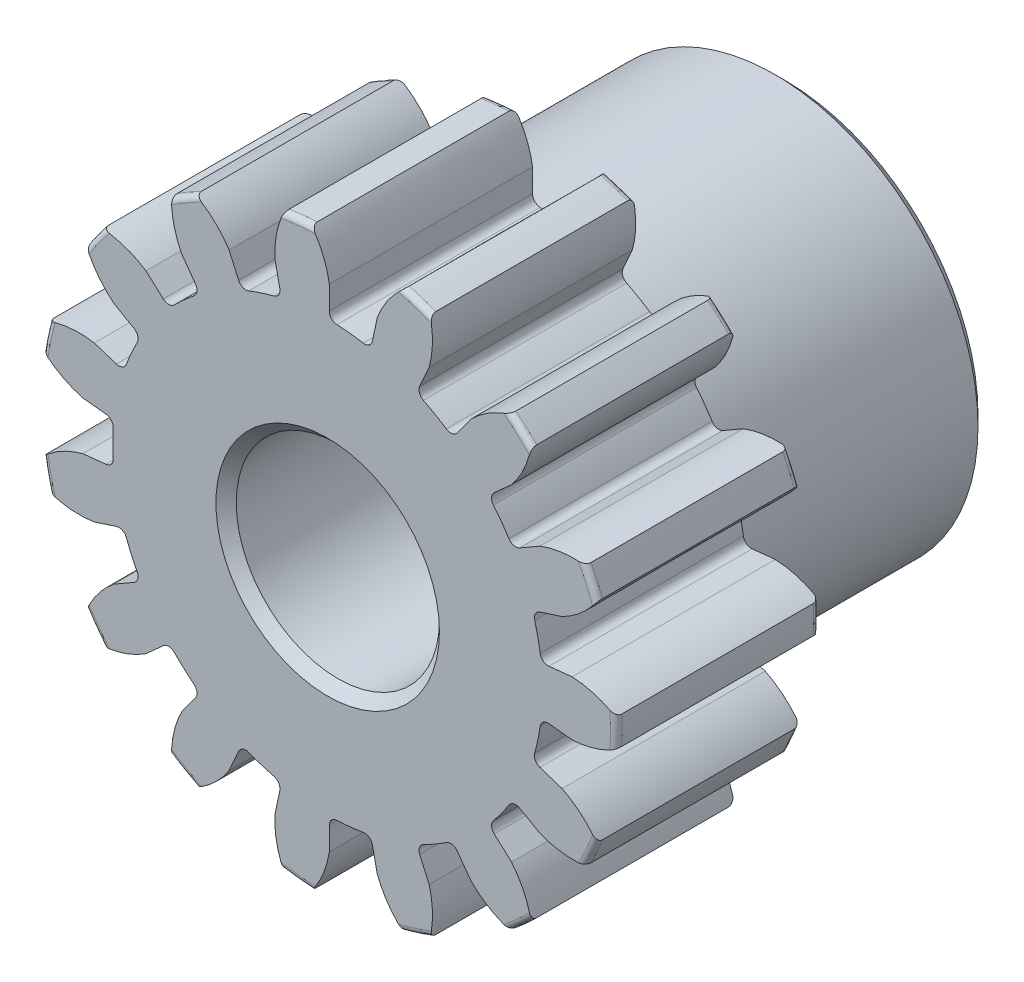
SolidWorks part; units mm, degrees
ref_plane "Front" through (0, 0, 0) normal (0, 0, 1) x (1, 0, 0)
ref_plane "Top" through (0, 0, 0) normal (0, 1, 0) x (1, 0, 0)
ref_plane "Right" through (0, 0, 0) normal (1, 0, 0) x (0, 0, -1)
sketch "Sketch1" plane through (0, 0, 0) normal (0, 0, 1) x (1, 0, 0)
  line L0 (-190.5, 0) -> (190.5, 0) construction
  circle A0 centre (0, 0) radius 9.017
  circle A1 centre (0, 0) radius 7.9375 construction
  circle A3 centre (0, 0) radius 6.713 construction
  dimension "D1" = 1.2245
  dimension "D2" = 2.304
  dimension "D3" = 1.0795
extrude "Boss-Extrude1" add sketch "Sketch1" against normal blind 6.35
sketch "Sketch2" plane through (0, 0, 0) normal (1, 0, 0) x (0, 0, -1)
  line L0 (6.35, 0) -> (14.2875, 0)
  line L1 (6.35, 0) -> (6.35, 6.35)
  line L2 (6.35, 6.35) -> (14.2875, 6.35)
  line L3 (14.2875, 6.35) -> (14.2875, 0)
  point P5 (14.2875, -6.35)
revolve "Revolve1" add sketch "Sketch2" angle 360 mid plane about L0
fillet "Fillet2" radius 0.1803 3 edges at (9.017, 0, -6.35) (9.017, 0, 0) (6.35, 0, -6.35)
sketch "Sketch3" plane through (0, 0, 0) normal (0, 0, 1) x (1, 0, 0)
  line L0 (0, 0) -> (0, 9.017) construction
  line L1 (-1.9241, 7.4399) -> (0, 7.9375)
  line L2 (-9.5921, 7.9375) -> (9.5921, 7.9375) construction
  line L3 (-9.2865, 5.5358) -> (9.2865, 10.3392) construction
  line L4 (-1.9241, 7.4399) -> (0, 0) construction
  line L5 (-4.7531, 6.0384) -> (0, 0) construction
  line L6 (-4.7531, 6.0384) -> (-0.6929, 9.2344) construction
  line L7 (-1.3417, 7.5666) -> (0, 0) construction
  line L8 (-1.3417, 7.5666) -> (0.0282, 7.8095) construction
  arc A0 (-1.9241, 7.4399) -> (-4.7531, 6.0384) centre (0, 0) ccw
  circle A1 centre (0, 0) radius 7.9375 construction
  circle A2 centre (0, 0) radius 7.6847 construction
  arc A3 (-1.9241, 7.4399) -> (-1.3417, 7.5666) centre (0, 0) cw
  circle A4 centre (0, 0) radius 9.017 construction
  point P6 (0, 7.9375)
  dimension "D1" = 1.9874
  dimension "D3" = 5.1672
  dimension "D5" = 1.3912
  dimension "D2" = 3.1798
  dimension "D4" = 0.5962
sketch "Sketch4" plane through (0, 0, 0) normal (0, 0, 1) x (1, 0, 0)
  line L0 (0, 0) -> (0.8252, 7.8508) construction
  line L1 (0.0499, 7.6845) -> (0.0499, 6.7128)
  line L2 (0, 7.9375) -> (1.6503, 7.764) construction
  line L3 (1.5489, 7.527) -> (1.3468, 6.5765)
  line L4 (0.0499, 6.7128) -> (0, 0) construction
  line L5 (0, 0) -> (0, 9.017) construction
  arc A0 (1.3468, 6.5765) -> (0.0499, 6.7128) centre (0, 0) ccw
  arc A1 (0, 7.9375) -> (1.6503, 7.764) centre (0, 0) cw construction
  circle A2 centre (0, 0) radius 7.9375 construction
  circle A3 centre (0, 0) radius 7.6847 construction
  circle A4 centre (0, 0) radius 6.713 construction
  arc A5 (2.5977, 8.8885) -> (-0.6929, 9.2344) centre (0, 0) ccw
  spline S0 degree 2 poles (-0.6929, 9.2344) (-0.0803, 8.5395) (0.0499, 7.6845) knots 0 0 0 1 1 1
  spline S1 degree 2 poles (2.5977, 8.8885) (1.854, 8.3362) (1.5489, 7.527) knots 0 0 0 1 1 1
  dimension "D1" = 1.6624
extrude "Cut-Extrude1" cut sketch "Sketch4" against normal through all
fillet "Fillet1" radius 0.2494 2 edges at (1.3468, 6.5765, -3.175) (0.0499, 6.7128, -3.175)
pattern_circular "CirPattern1" count 15 over 360 about axis through (0, 0, -6.35) along (0, 0, 1) of "Cut-Extrude1", "Fillet1"
sketch "Sketch5" plane through (0, 0, 0) normal (0, 0, 1) x (1, 0, 0)
  circle A0 centre (0, 0) radius 3.175
  circle A1 centre (0, 0) radius 3.175 construction
  dimension "Bore Min" = 6.35
  dimension "Bore Max" = 6.35
extrude "Cut-Extrude2" cut sketch "Sketch5" against normal through all
chamfer "Chamfer1" distance 0.3175 angle 45 3 edges at (6.35, 0, -14.2875) (3.175, 0, 0) (3.175, 0, -14.2875)
sketch "Pitch Dia" plane through (0, 0, 0) normal (0, 0, 1) x (1, 0, 0)
  circle A0 centre (0, 0) radius 7.9375 construction
  circle A1 centre (0, 0) radius 7.9375
equation "\"D1@Boss-Extrude1\" = \"Face Wd@Sketch2\""
equation "\"D2@Sketch3\" = \"D1@Sketch3\"*1.6"
equation "\"D3@Sketch3\" = \"D1@Sketch3\"+\"D2@Sketch3\""
equation "\"D4@Sketch3\" = \"D1@Sketch3\"*.3"
equation "\"D5@Sketch3\" = \"D1@Sketch3\"-\"D4@Sketch3\""
equation "\"D1@Sketch4\" = 1.5708/(\"Number of Teeth@Sketch1\"/\"Ptich Dia@Sketch1\")"
equation "\"D1@Chamfer1\" = \"B Hub Dia@Sketch2\"*.025"
equation "\"D1@CirPattern1\" = \"Number of Teeth@Sketch1\""
equation "\"D1@Fillet1\" = \"D1@Sketch4\"*.15"
equation "\"D1@Fillet2\" = \"OD@Sketch1\"*.01"
equation "\"D1@Sketch1\" = 1.157/(\"Number of Teeth@Sketch1\"/\"Ptich Dia@Sketch1\")"
